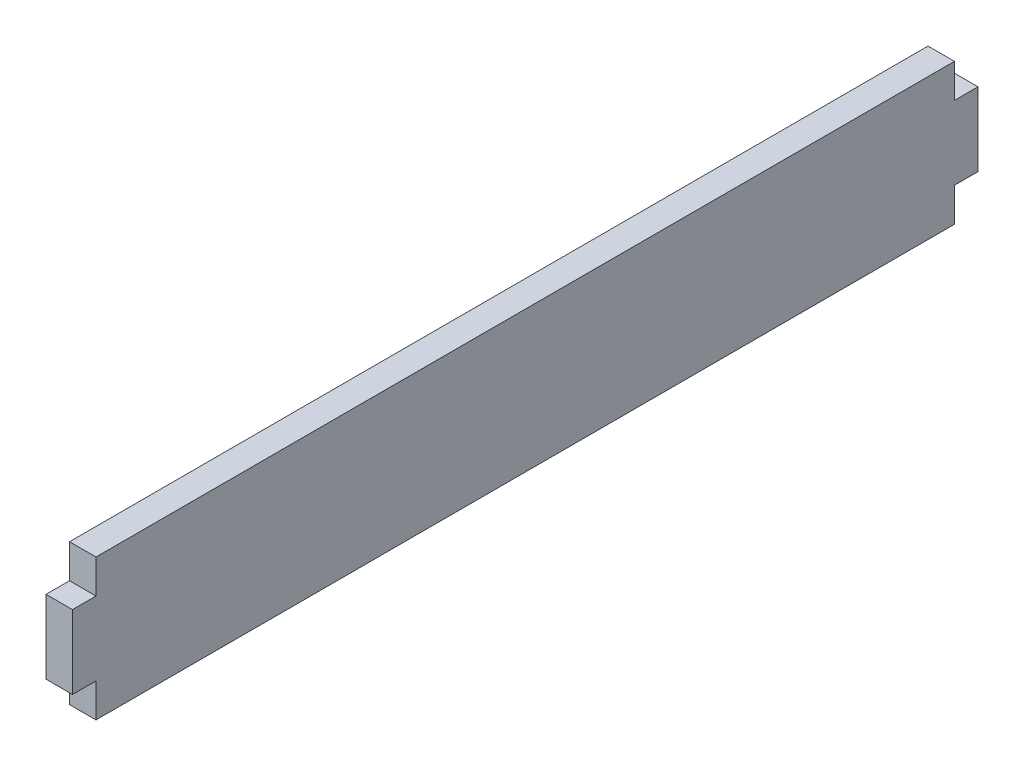
SolidWorks part; units mm, degrees
ref_plane "Front Plane" through (0, 0, 0) normal (0, 0, 1) x (1, 0, 0)
ref_plane "Top Plane" through (0, 0, 0) normal (0, 1, 0) x (1, 0, 0)
ref_plane "Right Plane" through (0, 0, 0) normal (1, 0, 0) x (0, 0, -1)
sketch "Sketch1" plane through (0, 0, 0) normal (1, 0, 0) x (0, 0, -1)
  line L0 (271.6459, 52.2461) -> (271.6459, 153.8243) construction
  line L15 (-20.3541, 148.2461) -> (563.6459, 148.2461)
  line L16 (-20.3541, 148.2461) -> (-20.3541, 125.2461)
  line L17 (-20.3541, 52.2461) -> (563.6459, 52.2461)
  line L18 (563.6459, 148.2461) -> (563.6459, 125.2461)
  line L19 (563.6459, 125.2461) -> (579.6459, 125.2461)
  line L21 (563.6459, 75.2461) -> (579.6459, 75.2461)
  line L22 (579.6459, 125.2461) -> (579.6459, 75.2461)
  line L25 (-20.3541, 125.2461) -> (-36.3541, 125.2461)
  line L26 (-20.3541, 75.2461) -> (-36.3541, 75.2461)
  line L27 (-36.3541, 125.2461) -> (-36.3541, 75.2461)
  line L28 (-20.3541, 75.2461) -> (-20.3541, 52.2461)
  line L29 (563.6459, 75.2461) -> (563.6459, 52.2461)
  point P5 (563.6459, 100.2461)
  dimension "D1" = 584
  dimension "D2" = 96
  dimension "D4" = 50
extrude "Boss-Extrude1" add sketch "Sketch1" along normal blind 18
